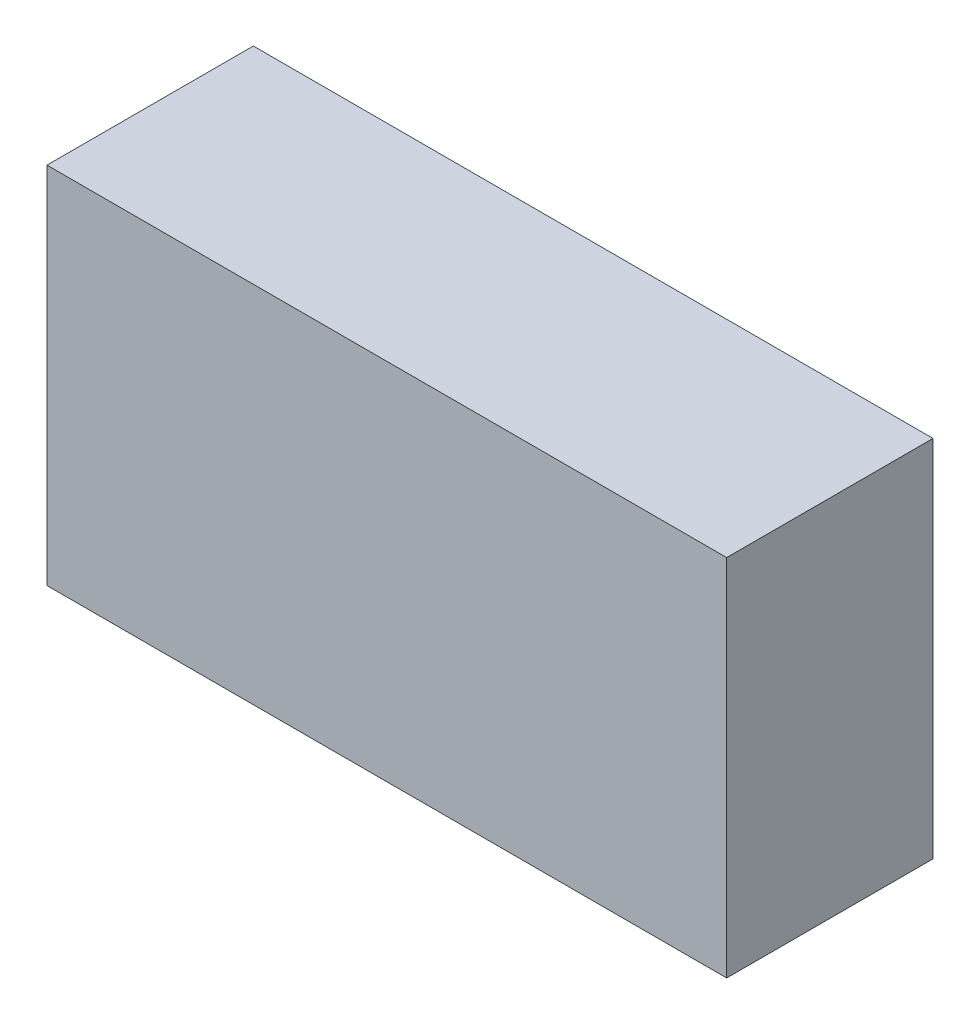
SolidWorks part; units mm, degrees
ref_plane "Ebene vorne" through (0, 0, 0) normal (0, 0, 1) x (1, 0, 0)
ref_plane "Ebene oben" through (0, 0, 0) normal (0, 1, 0) x (1, 0, 0)
ref_plane "Ebene rechts" through (0, 0, 0) normal (1, 0, 0) x (0, 0, -1)
sketch "Skizze1" plane through (0, 0, 0) normal (0, 0, 1) x (1, 0, 0)
  line L1 (0, 0) -> (56, 0)
  line L2 (0, 0) -> (0, 30)
  line L3 (0, 30) -> (56, 30)
  line L4 (56, 0) -> (56, 30)
  dimension "D1" = 30
  dimension "D2" = 56
extrude "Aufsatz-Linear austragen1" add sketch "Skizze1" along normal blind 17
ref_plane "Ebene1" through (0, 0, 17) normal (0, 0, -1) x (-1, 0, 0)
